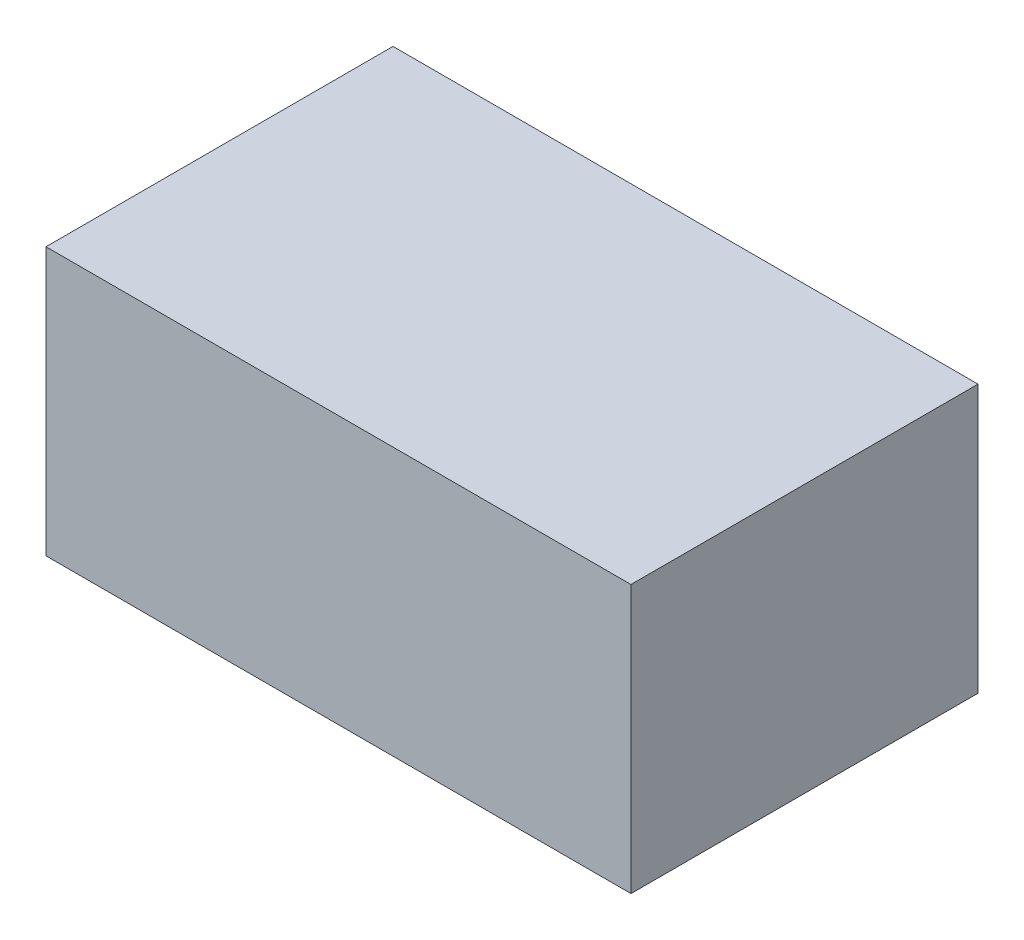
SolidWorks part; units mm, degrees
ref_plane "Front Plane" through (0, 0, 0) normal (0, 0, 1) x (1, 0, 0)
ref_plane "Top Plane" through (0, 0, 0) normal (0, 1, 0) x (1, 0, 0)
ref_plane "Right Plane" through (0, 0, 0) normal (1, 0, 0) x (0, 0, -1)
sketch "Sketch1" plane through (0, 0, 0) normal (0, 0, 1) x (1, 0, 0)
  line L1 (-29.5, 13.5) -> (29.5, 13.5)
  line L2 (-29.5, 13.5) -> (-29.5, -13.5)
  line L3 (-29.5, -13.5) -> (29.5, -13.5)
  line L4 (29.5, 13.5) -> (29.5, -13.5)
  line L5 (-29.5, 13.5) -> (29.5, -13.5) construction
  line L6 (-29.5, -13.5) -> (29.5, 13.5) construction
  point P0 (0, 0)
extrude "Boss-Extrude1" add sketch "Sketch1" along normal blind 35
